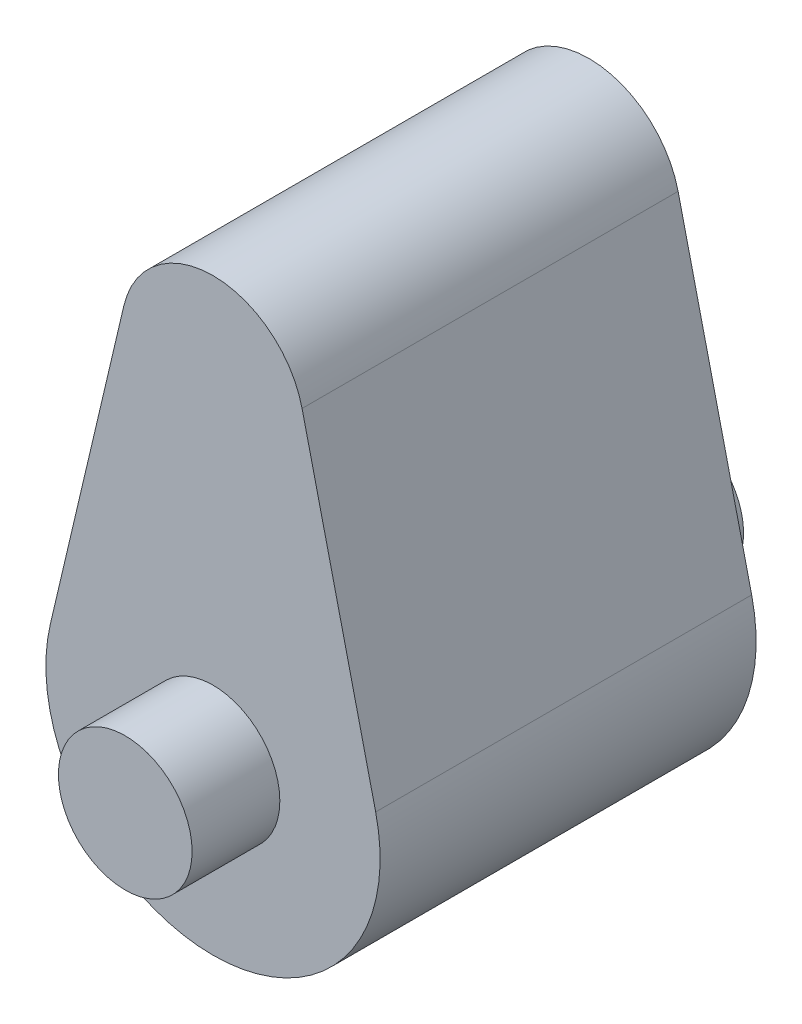
SolidWorks part; units mm, degrees
ref_plane "Front Plane" through (0, 0, 0) normal (0, 0, 1) x (1, 0, 0)
ref_plane "Top Plane" through (0, 0, 0) normal (0, 1, 0) x (1, 0, 0)
ref_plane "Right Plane" through (0, 0, 0) normal (1, 0, 0) x (0, 0, -1)
sketch "Sketch1" plane through (0, 0, 0) normal (0, 0, 1) x (1, 0, 0)
  circle A0 centre (0, 0) radius 8
extrude "Boss-Extrude1" add sketch "Sketch1" along normal blind 66
ref_plane "Plane1" through (0, 0, 33) normal (0, 0, 1) x (1, 0, 0)
sketch "Sketch2" plane through (0, 0, 33) normal (0, 0, 1) x (1, 0, 0)
  line L0 (-10.6622, 42.0022) -> (-19.4682, 4.5813)
  line L1 (10.6622, 42.0022) -> (19.4682, 4.5813)
  arc A0 (-19.4682, 4.5813) -> (19.4682, 4.5813) centre (0, 0) ccw
  arc A1 (10.6622, 42.0022) -> (-10.6622, 42.0022) centre (0, 39.4932) ccw
extrude "Boss-Extrude2" add sketch "Sketch2" along normal mid plane 45
